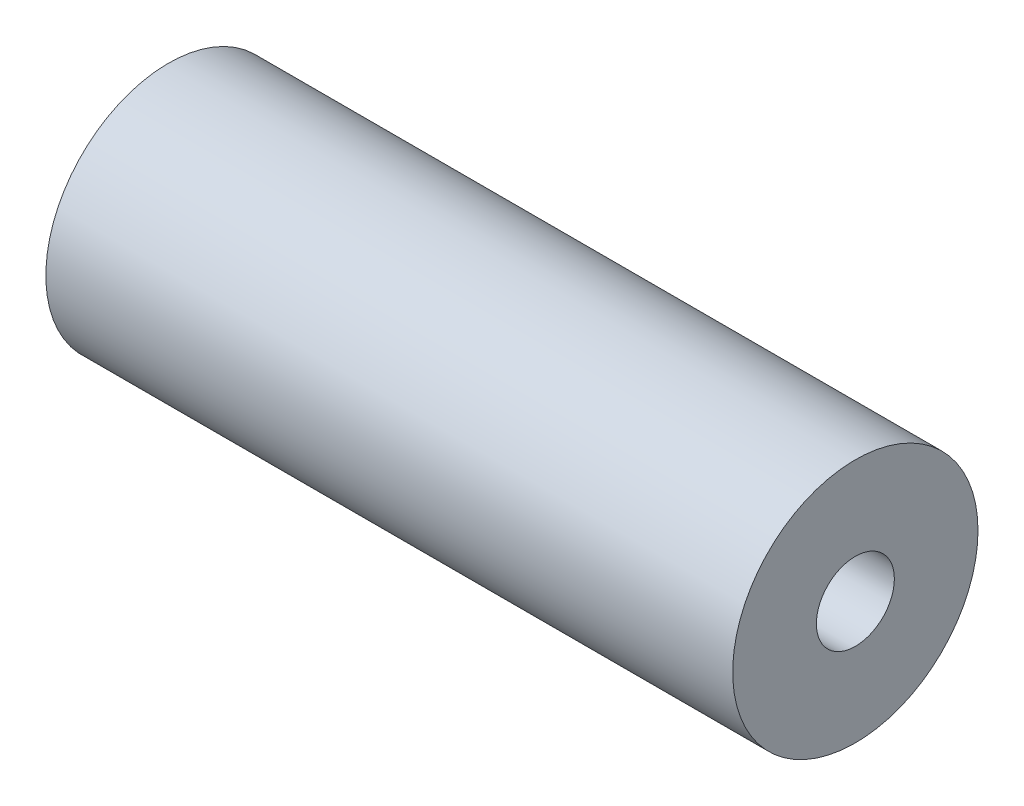
SolidWorks part; units mm, degrees
material "6061-T6 (SS)"
ref_plane "Front Plane" through (0, 0, 0) normal (0, 0, 1) x (1, 0, 0)
ref_plane "Top Plane" through (0, 0, 0) normal (0, 1, 0) x (1, 0, 0)
ref_plane "Right Plane" through (0, 0, 0) normal (1, 0, 0) x (0, 0, -1)
sketch "Sketch1" plane through (0, 0, 0) normal (1, 0, 0) x (0, 0, -1)
  circle A0 centre (0, 0) radius 6.35
  dimension "D1" = 12.7
extrude "Boss-Extrude1" add sketch "Sketch1" along normal mid plane 35.56
hole_wizard "Tap Drill for #10-32 Tap1" positions "Sketch2" profile "Sketch4" hole size "#10-32" standard "ANSI Inch"
sketch "Sketch2" plane through (17.78, 0, 0) normal (1, 0, 0) x (0, 0, -1)
  point P0 (0, 0)
sketch "Sketch4" plane through (17.78, 0, 0) normal (0, 1, 0) x (0, 0, -1)
  line L0 (0, 0) -> (0, 11.3733)
  line L1 (0, 11.3733) -> (2.0193, 10.16)
  line L2 (2.0193, 10.16) -> (2.0193, 0)
  line L5 (2.0193, 0) -> (0, 0)
  line L10 (0, 11.3733) -> (-2.0193, 10.16) construction
  line L11 (0, -6.35) -> (0, 107.95) construction
  dimension "Hole Dia." = 4.0386
  dimension "Hole Depth" = 10.16
  dimension "Drill Angle" = 118
mirror "Mirror1" about plane through (0, 0, 0) normal (1, 0, 0) of "Tap Drill for #10-32 Tap1"
